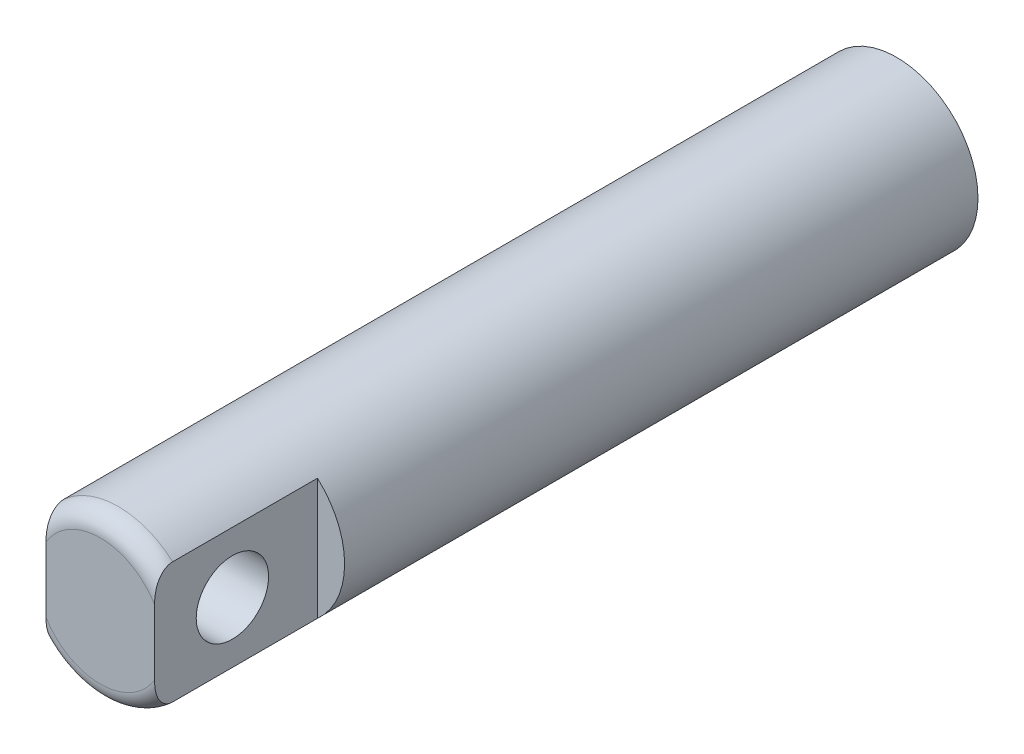
SolidWorks part; units mm, degrees
ref_plane "Спереди" through (0, 0, 0) normal (0, 0, 1) x (1, 0, 0)
ref_plane "Сверху" through (0, 0, 0) normal (0, 1, 0) x (1, 0, 0)
ref_plane "Справа" through (0, 0, 0) normal (1, 0, 0) x (0, 0, -1)
sketch "Эскиз1" plane through (0, 0, 0) normal (0, 0, 1) x (1, 0, 0)
  circle A0 centre (0, 0) radius 4.5
  dimension "D1" = 9
extrude "Бобышка-Вытянуть1" add sketch "Эскиз1" along normal blind 35
sketch "Эскиз2" plane through (0, 0, 35) normal (0, 0, 1) x (1, 0, 0)
  line L1 (3, -3.3541) -> (-3, -3.3541)
  line L2 (3, -3.3541) -> (3, 3.3541)
  line L3 (3, 3.3541) -> (-3, 3.3541)
  line L4 (-3, -3.3541) -> (-3, 3.3541)
  line L5 (3, -3.3541) -> (-3, 3.3541) construction
  line L6 (3, 3.3541) -> (-3, -3.3541) construction
  arc A0 (3, 3.3541) -> (-3, 3.3541) centre (0, 0) ccw
  circle A1 centre (0, 0) radius 4.5
  arc A2 (-3, -3.3541) -> (3, -3.3541) centre (0, 0) ccw
  circle M3 centre (0, 0) radius 4.5
  dimension "D2" = 6
  dimension "D1" = 0
extrude "Бобышка-Вытянуть2" add sketch "Эскиз2" along normal blind 9 contours L3 M3 | L4 L1 L2 L3 | L1 M3
sketch "Эскиз3" plane through (-3, 0, 0) normal (-1, 0, 0) x (0, 0, 1)
  line L0 (44, -3.3541) -> (44, 3.3541) construction
  circle A0 centre (39.7, 0) radius 2
  dimension "D1" = 4
  dimension "D2" = 4.3
extrude "Вырез-Вытянуть1" cut sketch "Эскиз3" against normal through all
fillet "Скругление1" radius 1 2 edges at (0, 4.5, 44) (0, -4.5, 44)
